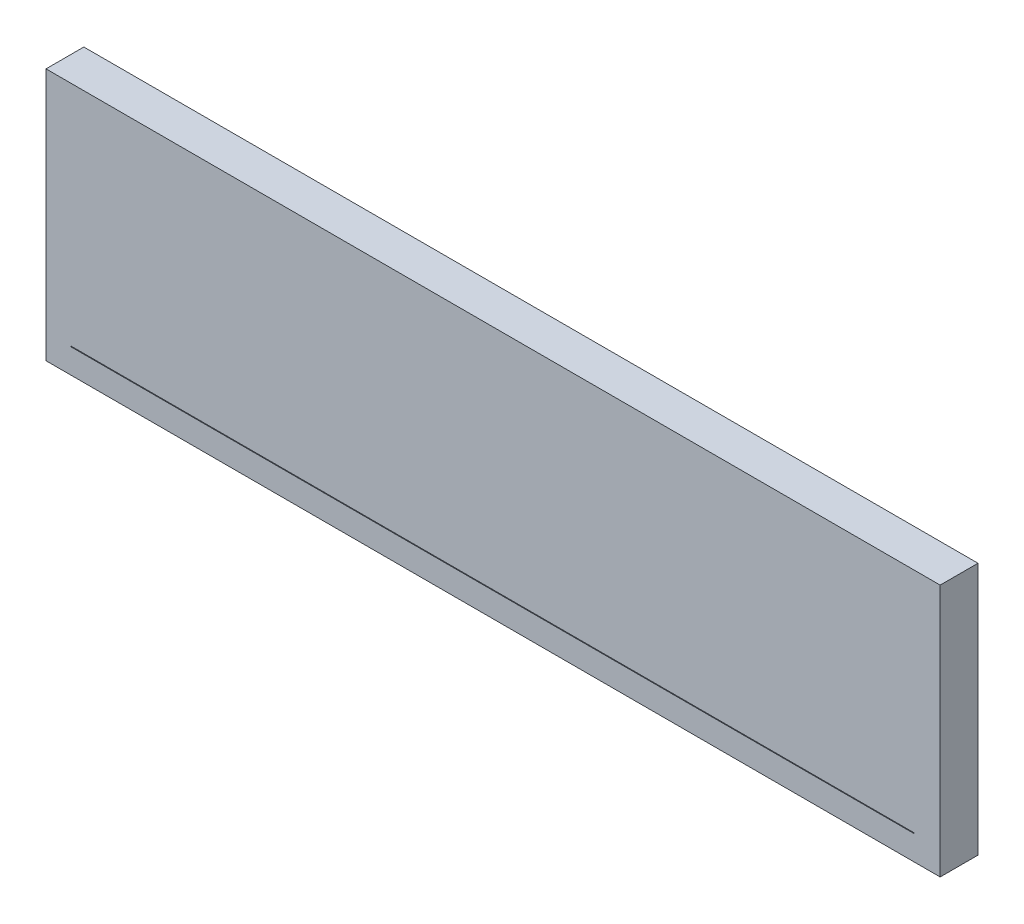
SolidWorks part; units mm, degrees
ref_plane "정면" through (0, 0, 0) normal (0, 0, 1) x (1, 0, 0)
ref_plane "윗면" through (0, 0, 0) normal (0, 1, 0) x (1, 0, 0)
ref_plane "우측면" through (0, 0, 0) normal (1, 0, 0) x (0, 0, -1)
sketch "스케치1" plane through (0, 0, 0) normal (0, 0, 1) x (1, 0, 0)
  line L1 (-16.7, -4.01) -> (16.7, -4.01)
  line L2 (-16.7, -4.01) -> (-16.7, 4.01)
  line L3 (-16.7, 4.01) -> (16.7, 4.01)
  line L4 (16.7, -4.01) -> (16.7, 4.01)
  line L5 (-16.7, -4.01) -> (16.7, 4.01) construction
  line L6 (-16.7, 4.01) -> (16.7, -4.01) construction
  point P0 (0, 0)
extrude "보스-돌출1" add sketch "스케치1" along normal blind 1
sketch "스케치2" plane through (0, 0, 1) normal (0, 0, 1) x (1, 0, 0)
  line L1 (-16.7, 4.01) -> (16.7, 4.01)
  line L3 (-16.7, 5.01) -> (17.7434, 5.01)
  line L4 (17.7434, 4.01) -> (17.7434, 5.01)
  line L6 (17.7434, 4.01) -> (17.7434, -5.011)
  line L7 (17.7434, -5.011) -> (16.7, -5.011)
  line L8 (16.7, 4.01) -> (16.7, -4.0376)
  line L9 (16.7, -5.011) -> (-17.7, -5.011)
  line L11 (16.7, -4.0376) -> (-16.7, -4.0376)
  line L12 (-17.7, -5.011) -> (-17.7, -4.0376)
  line L14 (-17.7, -4.0376) -> (-17.7, 5.01)
  line L15 (-17.7, 5.01) -> (-16.7, 5.01)
  line L16 (-16.7, -4.0376) -> (-16.7, 4.01)
  point P11 (0, 0)
extrude "보스-돌출2" add sketch "스케치2" against normal blind 1.5
